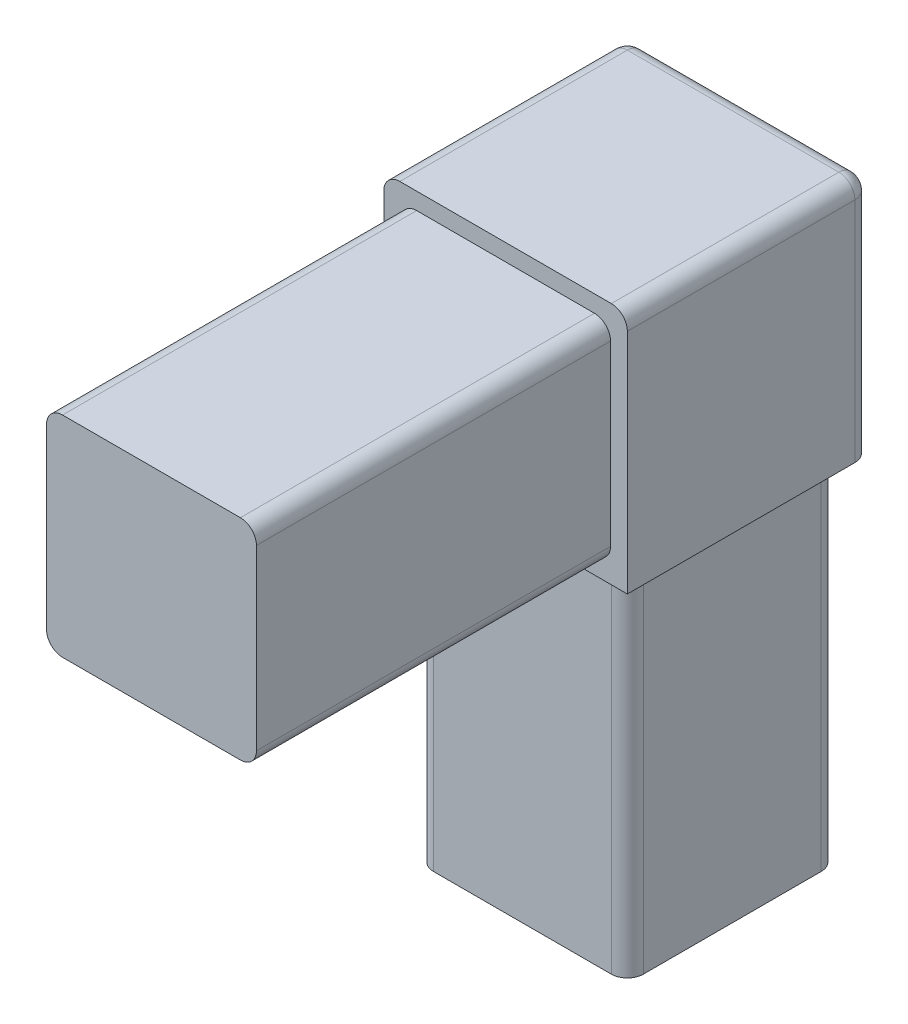
SolidWorks part; units mm, degrees
ref_plane "Front Plane" through (0, 0, 0) normal (0, 0, 1) x (1, 0, 0)
ref_plane "Top Plane" through (0, 0, 0) normal (0, 1, 0) x (1, 0, 0)
ref_plane "Right Plane" through (0, 0, 0) normal (1, 0, 0) x (0, 0, -1)
sketch "Sketch1" plane through (0, 0, 0) normal (0, 1, 0) x (1, 0, 0)
  line L1 (-8.3185, 8.3185) -> (8.3185, 8.3185)
  line L2 (-8.3185, 8.3185) -> (-8.3185, -8.3185)
  line L3 (-8.3185, -8.3185) -> (8.3185, -8.3185)
  line L4 (8.3185, 8.3185) -> (8.3185, -8.3185)
  line L5 (-8.3185, 8.3185) -> (8.3185, -8.3185) construction
  line L6 (-8.3185, -8.3185) -> (8.3185, 8.3185) construction
  point P0 (0, 0)
  dimension "D1" = 16.637
extrude "Boss-Extrude1" add sketch "Sketch1" along normal blind 28.067
sketch "Sketch2" plane through (0, 28.067, 0) normal (0, 1, 0) x (1, 0, 0)
  line L1 (-9.652, -9.652) -> (9.652, -9.652)
  line L2 (-9.652, -9.652) -> (-9.652, 9.652)
  line L3 (-9.652, 9.652) -> (9.652, 9.652)
  line L4 (9.652, -9.652) -> (9.652, 9.652)
  line L5 (-9.652, -9.652) -> (9.652, 9.652) construction
  line L6 (-9.652, 9.652) -> (9.652, -9.652) construction
  point P0 (0, 0)
  dimension "D1" = 19.304
  dimension "D2" = 19.304
extrude "Boss-Extrude2" add sketch "Sketch2" along normal blind 19.304
sketch "Sketch3" plane through (0, 0, 9.652) normal (0, 0, 1) x (1, 0, 0)
  line L0 (-9.652, 47.371) -> (9.652, 28.067) construction
  line L2 (-8.3185, 29.4005) -> (8.3185, 29.4005)
  line L3 (-8.3185, 29.4005) -> (-8.3185, 46.0375)
  line L4 (-8.3185, 46.0375) -> (8.3185, 46.0375)
  line L5 (8.3185, 29.4005) -> (8.3185, 46.0375)
  line L6 (-8.3185, 29.4005) -> (8.3185, 46.0375) construction
  line L7 (-8.3185, 46.0375) -> (8.3185, 29.4005) construction
  point P4 (0, 37.719)
  dimension "D1" = 16.637
extrude "Boss-Extrude3" add sketch "Sketch3" along normal blind 28.067
fillet "Fillet1" radius 1.27 13 edges at (-8.3185, 14.0335, 8.3185) (8.3185, 14.0335, 8.3185) (-8.3185, 14.0335, -8.3185) (8.3185, 14.0335, -8.3185) (-8.3185, 29.4005, 23.6855) (-8.3185, 46.0375, 23.6855) (8.3185, 29.4005, 23.6855) (8.3185, 46.0375, 23.6855) (-9.652, 47.371, 0) (-9.652, 37.719, -9.652) (9.652, 37.719, -9.652) (0, 47.371, -9.652) (9.652, 47.371, 0)
